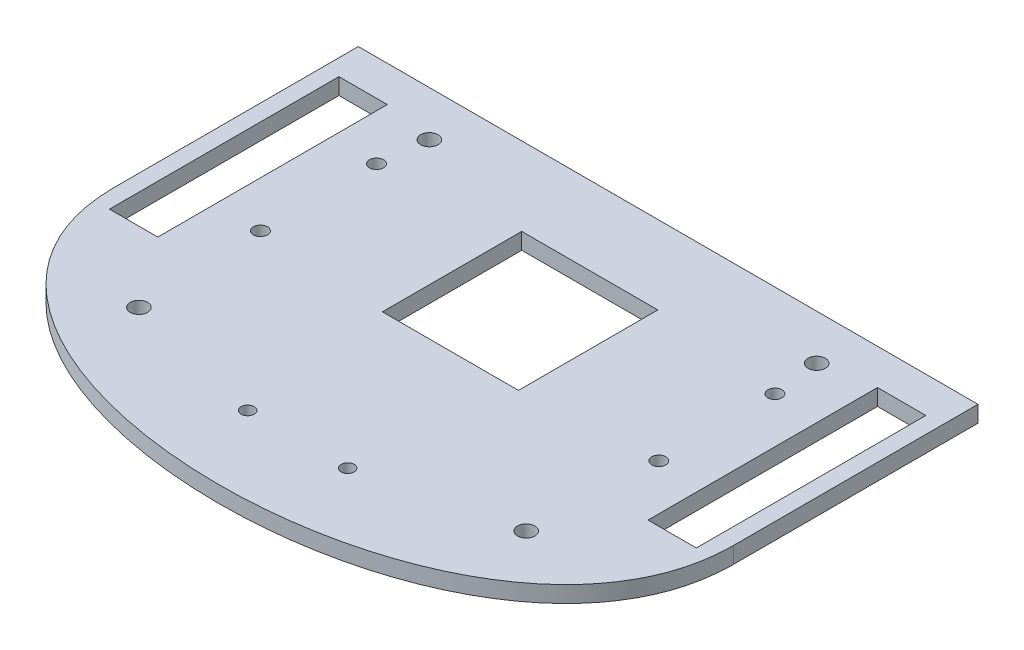
SolidWorks part; units mm, degrees
ref_plane "Front Plane" through (0, 0, 0) normal (0, 0, 1) x (1, 0, 0)
ref_plane "Top Plane" through (0, 0, 0) normal (0, 1, 0) x (1, 0, 0)
ref_plane "Right Plane" through (0, 0, 0) normal (1, 0, 0) x (0, 0, -1)
sketch "Sketch2" plane through (0, 0, 0) normal (0, 1, 0) x (1, 0, 0)
  line L4 (-48.006, -33.6908) -> (-48.006, 91.0268) construction
  line L5 (48.006, -34.798) -> (-48.006, -34.798) construction
  line L6 (48.006, -34.798) -> (48.006, 34.798) construction
  line L7 (48.006, 34.798) -> (-48.006, 34.798)
  line L8 (-48.006, -34.798) -> (-48.006, 34.798) construction
  line L9 (48.006, -34.798) -> (-48.006, 34.798) construction
  line L10 (48.006, 34.798) -> (-48.006, -34.798) construction
  line L11 (48.006, 148.5724) -> (48.006, -105.4276) construction
  line L12 (-48.006, 34.798) -> (-48.006, -3.048)
  line L13 (48.006, 34.798) -> (48.006, -3.048)
  spline S0 degree 3 poles (-48.006, -3.048) (-48.006, -45.3813) (48.006, -45.3813) (48.006, -3.048) knots 0 0 0 0 1 1 1 1
  point P0 (0, 0)
  dimension "D3" = 180
  dimension "D4" = 127
  dimension "D5" = 69.596
  dimension "D1" = 96.012
  dimension "D2" = 180
  dimension "D6" = 127
extrude "Boss-Extrude1" add sketch "Sketch2" along normal blind 2.54
sketch "Sketch3" plane through (0, 2.54, 0) normal (0, 1, 0) x (1, 0, 0)
  line L0 (0, 0) -> (0, 43.6246) construction
  line L1 (-45.466, 29.258) -> (-37.973, 29.258)
  line L2 (-45.466, 29.258) -> (-45.466, -6.302)
  line L3 (-45.466, -6.302) -> (-37.973, -6.302)
  line L4 (-37.973, 29.258) -> (-37.973, -6.302)
  line L5 (37.973, 29.258) -> (37.973, -6.302)
  line L6 (45.466, -6.302) -> (37.973, -6.302)
  line L7 (45.466, 29.258) -> (45.466, -6.302)
  line L8 (45.466, 29.258) -> (37.973, 29.258)
  line L9 (-48.006, 34.798) -> (-48.006, -3.048) construction
  line L10 (48.006, 34.798) -> (-48.006, 34.798) construction
  line L11 (-30.861, 20.4696) -> (-30.861, 2.4864) construction
  line L12 (30.861, 20.4696) -> (30.861, 2.4864) construction
  line L13 (-30, 27.798) -> (-30, -17.202) construction
  line L14 (30, 27.798) -> (30, -17.202) construction
  line L15 (0, -34.798) -> (28.6945, -34.798) construction
  line L16 (-10.541, 22.654) -> (10.541, 22.654)
  line L17 (-10.541, 22.654) -> (-10.541, 1.064)
  line L18 (-10.541, 1.064) -> (10.541, 1.064)
  line L19 (10.541, 22.654) -> (10.541, 1.064)
  circle A0 centre (-30.861, 20.4696) radius 1.0922
  circle A1 centre (-30.861, 2.4864) radius 1.0922
  circle A2 centre (-30, 27.798) radius 1.35
  circle A3 centre (30.861, 2.4864) radius 1.0922
  circle A4 centre (30.861, 20.4696) radius 1.0922
  circle A5 centre (-30, -17.202) radius 1.35
  circle A6 centre (30, -17.202) radius 1.35
  circle A7 centre (30, 27.798) radius 1.35
  circle A8 centre (-7.747, -22.606) radius 1.016
  circle A9 centre (7.747, -22.606) radius 1.016
  spline S1 degree 3 poles (-48.006, -3.048) (-48.006, -45.3813) (48.006, -45.3813) (48.006, -3.048) knots 0 0 0 0 1 1 1 1 construction
  point P14 (-41.7195, 29.258)
  point P20 (-30.861, 11.478)
  point P24 (-37.973, 11.478)
  point P36 (30.861, 11.478)
  dimension "D5" = 2.1844
  dimension "D6" = 2.1844
  dimension "D9" = 2.7
  dimension "D13" = 2.032
  dimension "D1" = 35.56
  dimension "D2" = 7.493
  dimension "D3" = 2.54
  dimension "D4" = 5.54
  dimension "D7" = 17.9832
  dimension "D8" = 7.112
  dimension "D10" = 7
  dimension "D11" = 30
  dimension "D12" = 45
  dimension "D14" = 20.32
  dimension "D15" = 21.59
  dimension "D16" = 20.32
  dimension "D17" = 15.494
  dimension "D18" = 12.144
  dimension "D19" = 12.192
extrude "Cut-Extrude1" cut sketch "Sketch3" against normal through all and the other way through all
